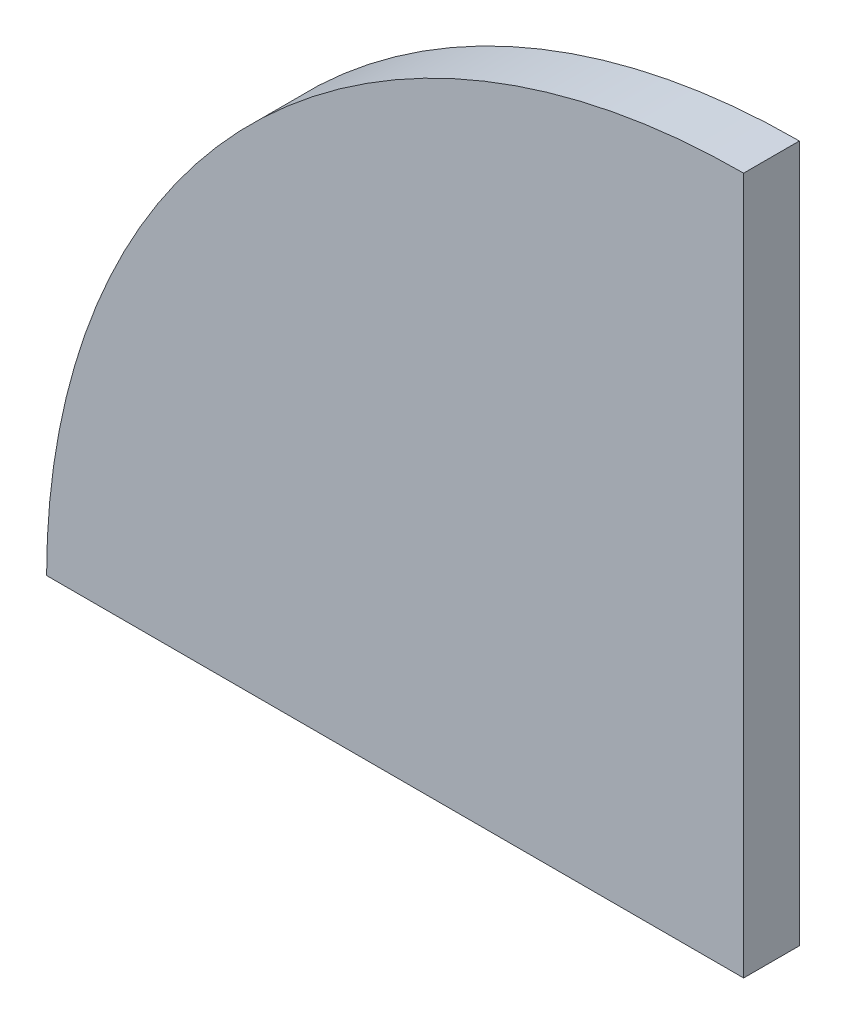
SolidWorks part; units mm, degrees
ref_plane "前视基准面" through (0, 0, 0) normal (0, 0, 1) x (1, 0, 0)
ref_plane "上视基准面" through (0, 0, 0) normal (0, 1, 0) x (1, 0, 0)
ref_plane "右视基准面" through (0, 0, 0) normal (1, 0, 0) x (0, 0, -1)
other "Configuration Table"
sketch "草图1" plane through (0, 0, 0) normal (0, 0, 1) x (1, 0, 0)
  line L0 (0, 0) -> (0, 25)
  line L1 (0, 0) -> (-25, 0)
  arc A0 (0, 25) -> (-25, 0) centre (0, 0) ccw
  dimension "D1" = 50
extrude "凸台-拉伸1" add sketch "草图1" along normal blind 2
